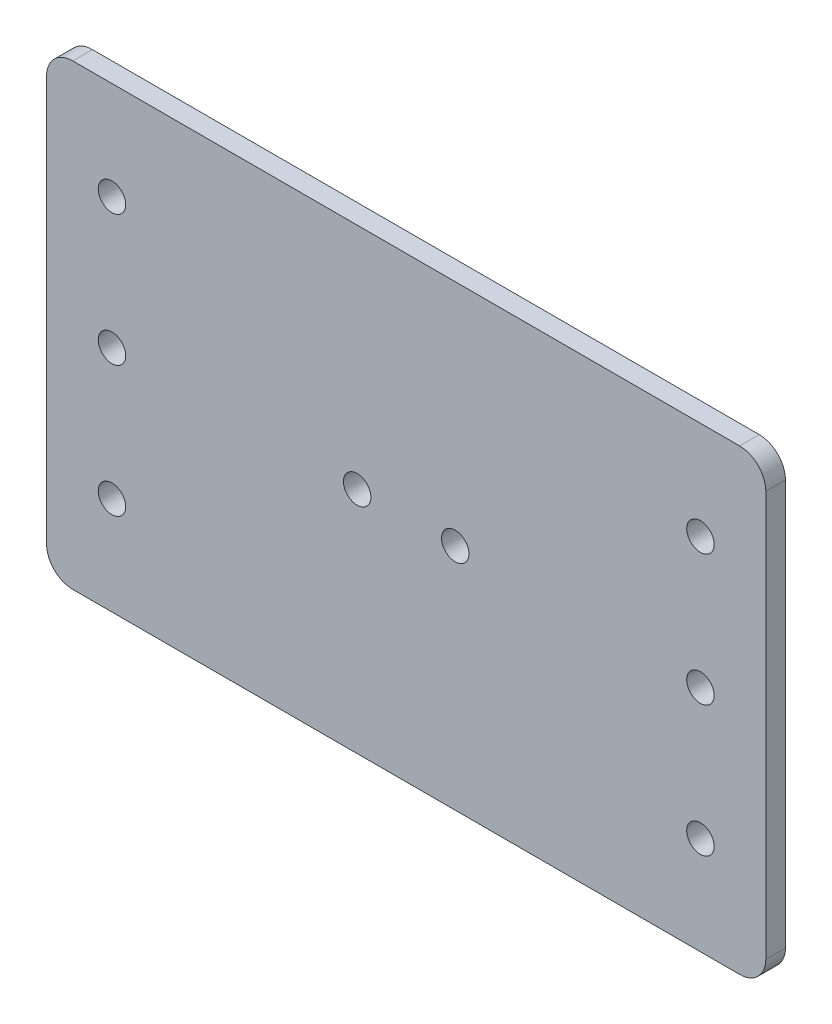
SolidWorks part; units mm, degrees
ref_plane "前视基准面" through (0, 0, 0) normal (0, 0, 1) x (1, 0, 0)
ref_plane "上视基准面" through (0, 0, 0) normal (0, 1, 0) x (1, 0, 0)
ref_plane "右视基准面" through (0, 0, 0) normal (1, 0, 0) x (0, 0, -1)
sketch "草图1" plane through (0, 0, 0) normal (0, 0, 1) x (1, 0, 0)
  line L0 (0, 35) -> (0, -35) construction
  line L1 (-55, 35) -> (55, 35)
  line L2 (-55, 35) -> (-55, -35)
  line L3 (-55, -35) -> (55, -35)
  line L4 (55, 35) -> (55, -35)
  line L5 (-55, 35) -> (55, -35) construction
  line L6 (-55, -35) -> (55, 35) construction
  circle A1 centre (45, 20) radius 2.1
  circle A2 centre (45, 0) radius 2.1
  circle A3 centre (45, -20) radius 2.1
  circle A4 centre (-45, 20) radius 2.1
  circle A5 centre (-45, 0) radius 2.1
  circle A6 centre (-45, -20) radius 2.1
  circle A9 centre (-7.5, 0) radius 2.1
  circle A11 centre (7.5, 0) radius 2.1
  point P0 (0, 0)
  dimension "D3" = 4.2
  dimension "D4" = 10
  dimension "D6" = 4.2
  dimension "D9" = 7.5
  dimension "D1" = 110
  dimension "D2" = 70
  dimension "D5" = 15
  dimension "D8" = 20
  dimension "D10" = 35
  dimension "D7" = 3
extrude "凸台-拉伸1" add sketch "草图1" along normal blind 3
fillet "圆角1" radius 4 4 edges at (55, 35, 1.5) (55, -35, 1.5) (-55, -35, 1.5) (-55, 35, 1.5)
